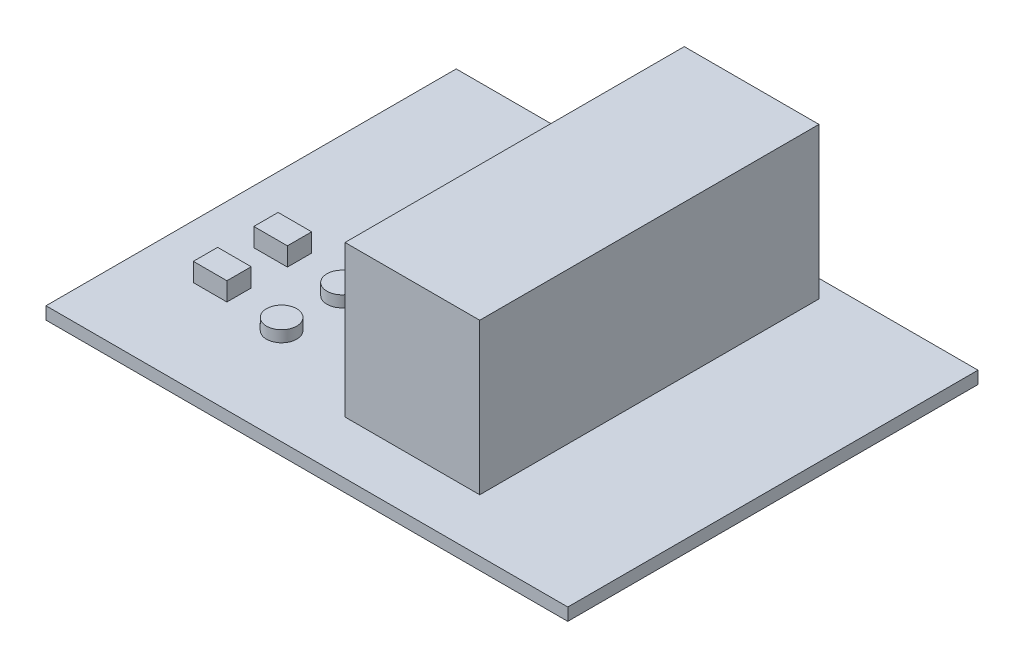
SolidWorks part; units mm, degrees
ref_plane "Front Plane" through (0, 0, 0) normal (0, 0, 1) x (1, 0, 0)
ref_plane "Top Plane" through (0, 0, 0) normal (0, 1, 0) x (1, 0, 0)
ref_plane "Right Plane" through (0, 0, 0) normal (1, 0, 0) x (0, 0, -1)
sketch "Sketch1" plane through (0, 0, 0) normal (0, 1, 0) x (1, 0, 0)
  line L1 (-34.515, -27.135) -> (34.515, -27.135)
  line L2 (-34.515, -27.135) -> (-34.515, 27.135)
  line L3 (-34.515, 27.135) -> (34.515, 27.135)
  line L4 (34.515, -27.135) -> (34.515, 27.135)
  line L5 (-34.515, -27.135) -> (34.515, 27.135) construction
  line L6 (-34.515, 27.135) -> (34.515, -27.135) construction
  point P0 (0, 0)
  dimension "D1" = 69.03
  dimension "D2" = 54.27
extrude "Boss-Extrude1" add sketch "Sketch1" along normal blind 1.65
sketch "Sketch2" plane through (0, 1.65, 0) normal (0, 1, 0) x (1, 0, 0)
  line L0 (-34.515, 27.135) -> (-34.515, -27.135) construction
  line L2 (-34.515, -27.135) -> (34.515, -27.135) construction
  line L5 (34.515, 27.135) -> (-34.515, 27.135) construction
  circle A0 centre (-16.095, -14.385) radius 2
  circle A1 centre (-16.095, -6.385) radius 2
  dimension "D1" = 18.42
  dimension "D3" = 8
  dimension "D2" = 12.75
extrude "Boss-Extrude2" add sketch "Sketch2" along normal blind 1.5
sketch "Sketch3" plane through (0, 1.65, 0) normal (0, 1, 0) x (1, 0, 0)
  line L0 (-34.515, -27.135) -> (34.515, -27.135) construction
  line L1 (-27.415, -11.53) -> (-22.975, -11.53)
  line L2 (-27.415, -11.53) -> (-27.415, -14.74)
  line L3 (-27.415, -14.74) -> (-22.975, -14.74)
  line L4 (-22.975, -11.53) -> (-22.975, -14.74)
  line L5 (-27.415, -11.53) -> (-22.975, -14.74) construction
  line L6 (-27.415, -14.74) -> (-22.975, -11.53) construction
  line L7 (-34.515, 27.135) -> (-34.515, -27.135) construction
  line L9 (-27.415, -3.53) -> (-22.975, -3.53)
  line L10 (-27.415, -3.53) -> (-27.415, -6.74)
  line L11 (-27.415, -6.74) -> (-22.975, -6.74)
  line L12 (-22.975, -3.53) -> (-22.975, -6.74)
  line L13 (-27.415, -3.53) -> (-22.975, -6.74) construction
  line L14 (-27.415, -6.74) -> (-22.975, -3.53) construction
  point P0 (-25.195, -13.135)
  point P9 (0, 0)
  point P10 (-25.195, -5.135)
  dimension "D1" = 14
  dimension "D2" = 9.32
  dimension "D3" = 4.44
  dimension "D4" = 3.21
  dimension "D5" = 3.21
  dimension "D6" = 4.44
  dimension "D7" = 8
extrude "Boss-Extrude3" add sketch "Sketch3" along normal blind 2.44
sketch "Sketch4" plane through (0, 1.65, 0) normal (0, 1, 0) x (1, 0, 0)
  line L0 (34.515, -27.135) -> (34.515, 27.135) construction
  line L1 (-1.985, 24.775) -> (15.835, 24.775)
  line L2 (-1.985, 24.775) -> (-1.985, -20.105)
  line L3 (-1.985, -20.105) -> (15.835, -20.105)
  line L4 (15.835, 24.775) -> (15.835, -20.105)
  line L5 (-34.515, -27.135) -> (34.515, -27.135) construction
  dimension "D1" = 17.82
  dimension "D2" = 44.88
  dimension "D3" = 18.68
  dimension "D4" = 7.03
extrude "Boss-Extrude4" add sketch "Sketch4" along normal blind 20
